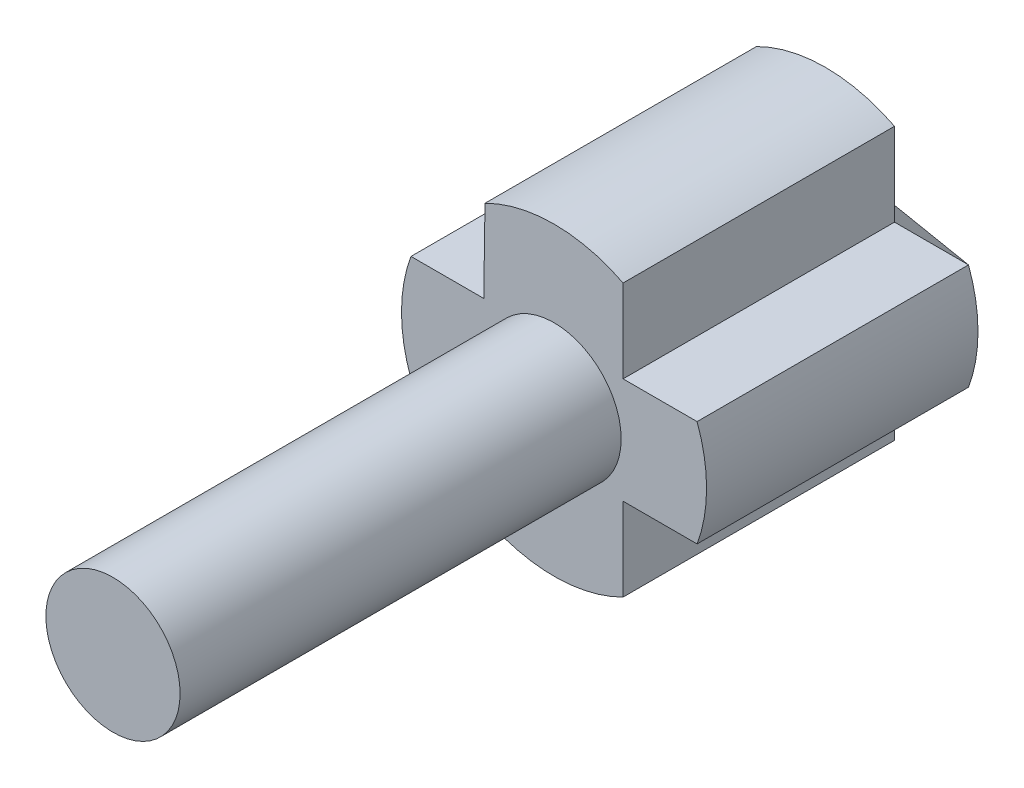
SolidWorks part; units mm, degrees
ref_plane "前视基准面" through (0, 0, 0) normal (0, 0, 1) x (1, 0, 0)
ref_plane "上视基准面" through (0, 0, 0) normal (0, 1, 0) x (1, 0, 0)
ref_plane "右视基准面" through (0, 0, 0) normal (1, 0, 0) x (0, 0, -1)
sketch "草图1" plane through (0, 0, 0) normal (0, 0, 1) x (1, 0, 0)
  circle A0 centre (0, 0) radius 19.783
extrude "凸台-拉伸1" add sketch "草图1" along normal blind 130
sketch "草图2" plane through (0, 0, 0) normal (0, 0, -1) x (-1, 0, 0)
  line L0 (-20.3514, 40.0924) -> (-20.3514, 15.6157)
  line L1 (20.3514, 40.0924) -> (20.717, 15.6157)
  line L2 (-42.1631, 15.6157) -> (-20.3514, 15.6157)
  line L3 (-42.1631, -15.6157) -> (-20.3514, -15.6157)
  line L4 (-20.3514, -15.6157) -> (-20.3514, -40.0924)
  line L5 (21.1835, -15.6157) -> (21.5397, -39.4667)
  line L6 (20.717, 15.6157) -> (42.1631, 15.6157)
  line L7 (21.1835, -15.6157) -> (42.1631, -15.6157)
  arc A0 (-42.1631, 15.6157) -> (-42.1631, -15.6157) centre (0, 0) ccw
  arc A1 (20.3514, 40.0924) -> (-20.3514, 40.0924) centre (0, 0) ccw
  arc A2 (42.1631, -15.6157) -> (42.1631, 15.6157) centre (0, 0) ccw
  arc A3 (-20.3514, -40.0924) -> (21.5397, -39.4667) centre (0, 0) ccw
extrude "凸台-拉伸2" add sketch "草图2" along normal blind 80
ref_plane "基准面1" through (0, 0, -100) normal (0, 0, -1) x (-1, 0, 0)
sketch "草图3" plane through (0, 0, -100) normal (0, 0, -1) x (-1, 0, 0)
  point P0 (0, 0)
sketch "草图4" plane through (0, 0, -80) normal (0, 0, -1) x (-1, 0, 0)
  line L8 (-20.3514, 15.6157) -> (-42.1631, 15.6157)
  line L9 (-42.1631, -15.6157) -> (-20.3514, -15.6157)
  line L10 (-20.3514, -15.6157) -> (-20.3514, -40.0924)
  line L11 (21.5397, -39.4667) -> (21.1835, -15.6157)
  line L12 (21.1835, -15.6157) -> (42.1631, -15.6157)
  line L13 (42.1631, 15.6157) -> (20.717, 15.6157)
  line L14 (20.717, 15.6157) -> (20.3514, 40.0924)
  line L15 (-20.3514, 40.0924) -> (-20.3514, 15.6157)
  line L16 (-20.3514, 15.6157) -> (-42.1631, 15.6157)
  line L17 (-42.1631, -15.6157) -> (-20.3514, -15.6157)
  line L18 (-20.3514, -15.6157) -> (-20.3514, -40.0924)
  line L19 (21.5397, -39.4667) -> (21.1835, -15.6157)
  line L20 (21.1835, -15.6157) -> (42.1631, -15.6157)
  line L21 (42.1631, 15.6157) -> (20.717, 15.6157)
  line L22 (20.717, 15.6157) -> (20.3514, 40.0924)
  line L23 (-20.3514, 40.0924) -> (-20.3514, 15.6157)
  arc A4 (-42.1631, 15.6157) -> (-42.1631, -15.6157) centre (0, 0) ccw
  arc A5 (-20.3514, -40.0924) -> (21.5397, -39.4667) centre (0, 0) ccw
  arc A6 (42.1631, -15.6157) -> (42.1631, 15.6157) centre (0, 0) ccw
  arc A7 (20.3514, 40.0924) -> (-20.3514, 40.0924) centre (0, 0) ccw
  arc A8 (-42.1631, 15.6157) -> (-42.1631, -15.6157) centre (0, 0) ccw
  arc A9 (-20.3514, -40.0924) -> (21.5397, -39.4667) centre (0, 0) ccw
  arc A10 (42.1631, -15.6157) -> (42.1631, 15.6157) centre (0, 0) ccw
  arc A11 (20.3514, 40.0924) -> (-20.3514, 40.0924) centre (0, 0) ccw
  dimension "D1" = 0
loft "放样1" add profiles "草图4", "草图3"
